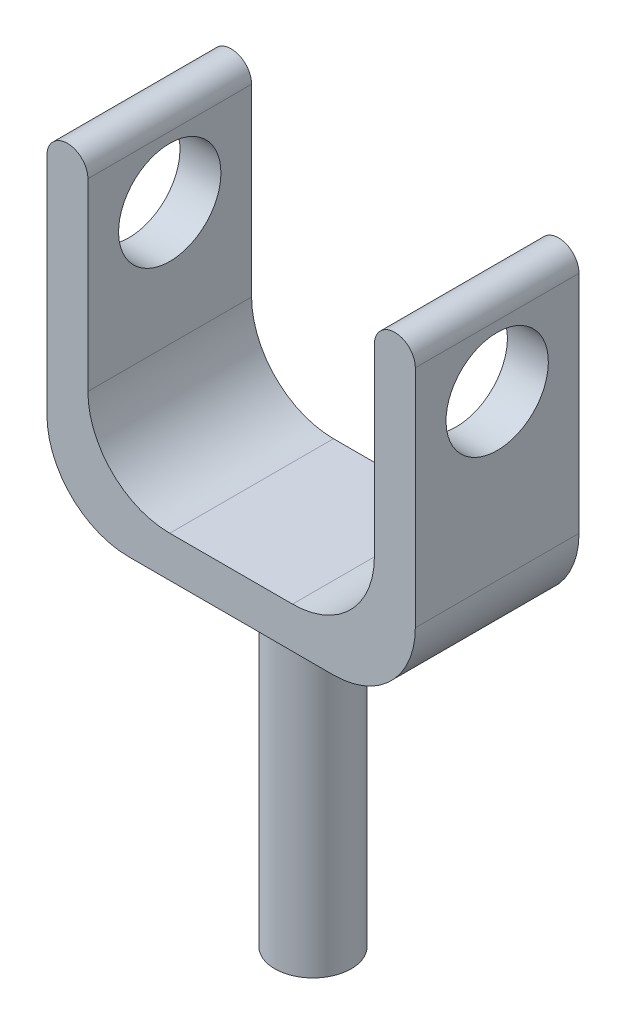
SolidWorks part; units mm, degrees
ref_plane "Front Plane" through (0, 0, 0) normal (0, 0, 1) x (1, 0, 0)
ref_plane "Top Plane" through (0, 0, 0) normal (0, 1, 0) x (1, 0, 0)
ref_plane "Right Plane" through (0, 0, 0) normal (1, 0, 0) x (0, 0, -1)
sketch "Sketch1" plane through (0, 0, 0) normal (0, 0, 1) x (1, 0, 0)
  line L0 (-40, 0) -> (40, 0) construction
  line L1 (40, 0) -> (40, 70) construction
  line L2 (-40, 0) -> (-40, 70) construction
  line L3 (35, 5) -> (35, 70)
  line L4 (-35, 5) -> (35, 5)
  line L5 (-35, 5) -> (-35, 70)
  line L6 (45, -5) -> (45, 70)
  line L7 (-45, -5) -> (45, -5)
  line L8 (-45, -5) -> (-45, 70)
  arc A0 (35, 70) -> (45, 70) centre (40, 70) cw
  arc A1 (-35, 70) -> (-45, 70) centre (-40, 70) ccw
  dimension "D1" = 70
  dimension "D2" = 70
  dimension "D3" = 80
  dimension "D4" = 40
  dimension "D5" = 5
  dimension "D6" = 5
extrude "Boss-Extrude1" add sketch "Sketch1" along normal mid plane 40
sketch "Sketch2" plane through (0, -5, 0) normal (0, -1, 0) x (1, 0, 0)
  circle A0 centre (0, 0) radius 9.3485
  dimension "D1" = 18.697
extrude "Boss-Extrude2" add sketch "Sketch2" along normal blind 80
fillet "Fillet1" radius 20 4 edges at (-35, 5, 0) (35, 5, 0) (45, -5, 0) (-45, -5, 0)
sketch "Sketch3" plane through (45, 0, 0) normal (1, 0, 0) x (0, 0, -1)
  line L0 (-20, 15) -> (-20, 70) construction
  line L1 (20, -5) -> (-20, -5) construction
  circle A0 centre (0, 55) radius 12.5
  dimension "D1" = 25
  dimension "D2" = 20
  dimension "D3" = 60
extrude "Cut-Extrude1" cut sketch "Sketch3" against normal through all both and the other way through all
scale "Scale1" scale about centroid uniform scaling yes scale factor 0.5
